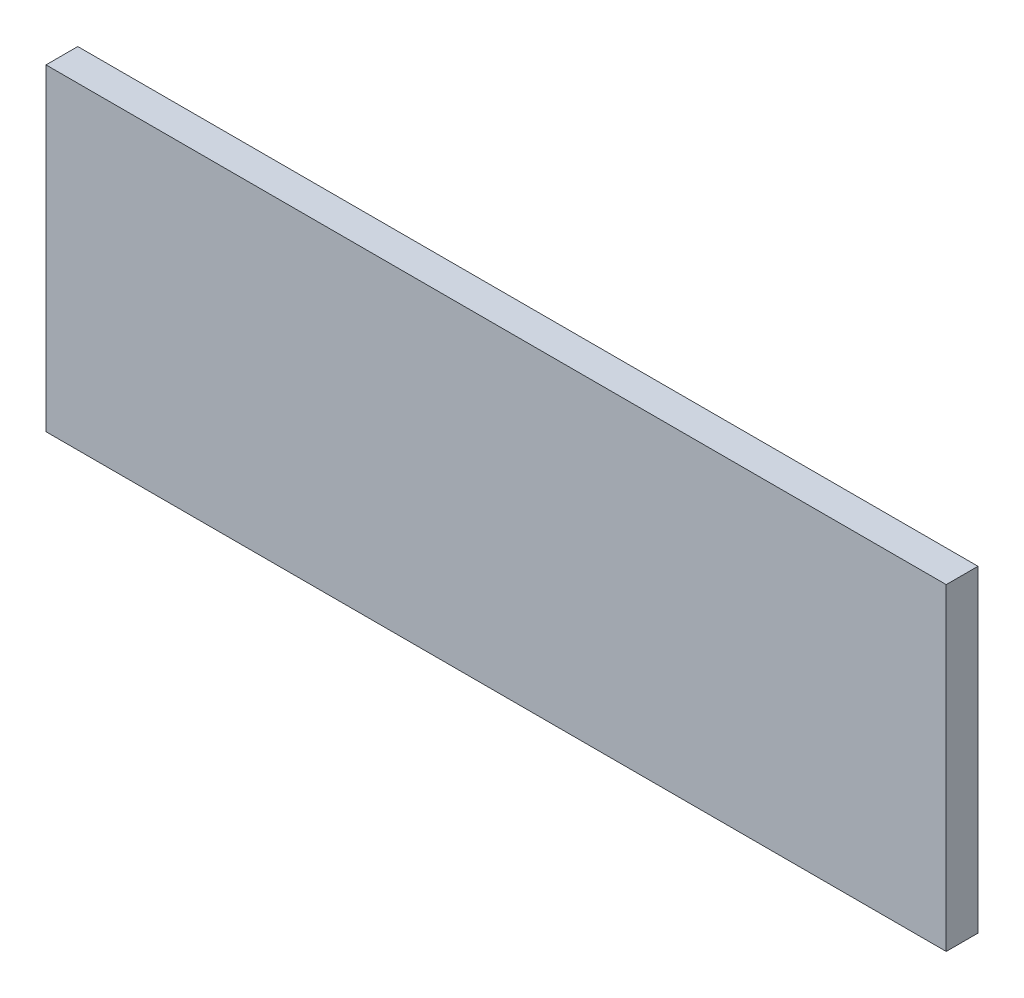
SolidWorks part; units mm, degrees
ref_plane "Front Plane" through (0, 0, 0) normal (0, 0, 1) x (1, 0, 0)
ref_plane "Top Plane" through (0, 0, 0) normal (0, 1, 0) x (1, 0, 0)
ref_plane "Right Plane" through (0, 0, 0) normal (1, 0, 0) x (0, 0, -1)
sketch "Sketch1" plane through (0, 0, 0) normal (0, 0, 1) x (1, 0, 0)
  line L1 (0, 0) -> (170, 0)
  line L2 (0, 0) -> (0, 60)
  line L3 (0, 60) -> (170, 60)
  line L4 (170, 0) -> (170, 60)
  dimension "D1" = 170
  dimension "D2" = 60
extrude "Boss-Extrude1" add sketch "Sketch1" along normal blind 6
